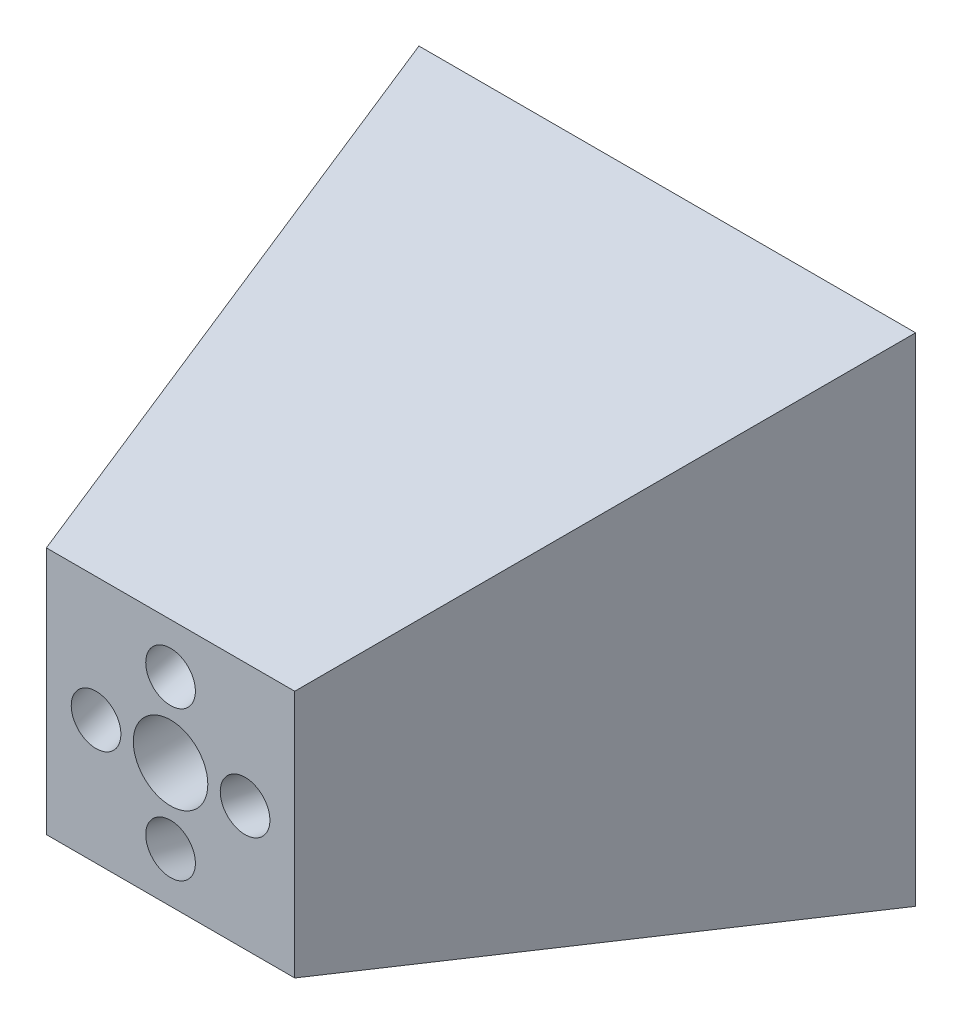
SolidWorks part; units mm, degrees
ref_plane "Front Plane" through (0, 0, 0) normal (0, 0, 1) x (1, 0, 0)
ref_plane "Top Plane" through (0, 0, 0) normal (0, 1, 0) x (1, 0, 0)
ref_plane "Right Plane" through (0, 0, 0) normal (1, 0, 0) x (0, 0, -1)
sketch "Sketch1" plane through (0, 0, 0) normal (0, 0, 1) x (1, 0, 0)
  line L1 (-25000, 25000) -> (25000, 25000)
  line L2 (-25000, 25000) -> (-25000, -25000)
  line L3 (-25000, -25000) -> (25000, -25000)
  line L4 (25000, 25000) -> (25000, -25000)
  point P4 (0, 25000)
  point P5 (25000, 0)
  dimension "D1" = 50000
ref_plane "Plane1" through (0, 0, -100000) normal (0, 0, 1) x (1, 0, 0)
sketch "Sketch2" plane through (0, 0, -100000) normal (0, 0, 1) x (1, 0, 0)
  line L1 (-50000, -50000) -> (50000, -50000)
  line L2 (-50000, -50000) -> (-50000, 50000)
  line L3 (-50000, 50000) -> (50000, 50000)
  line L4 (50000, -50000) -> (50000, 50000)
  line L5 (-50000, -50000) -> (50000, 50000) construction
  line L6 (-50000, 50000) -> (50000, -50000) construction
  point P0 (0, 0)
  dimension "D1" = 100000
loft "Loft1" add profiles "Sketch1", "Sketch2"
sketch "Sketch4" plane through (0, 0, -100000) normal (0, 0, -1) x (-1, 0, 0)
  point P5 (0, 0)
  point P6 (0, 0)
  point P7 (0, 0)
  point P17 (0, 0)
sketch "Sketch12" plane through (0, 0, 0) normal (0, 1, 0) x (1, 0, 0)
  line L0 (0, 100000) -> (0, 0)
sketch "Sketch13" plane through (0, 0, -100000) normal (0, 0, -1) x (-1, 0, 0)
  circle A0 centre (0, 0) radius 7500
  dimension "D1" = 15000
sweep "Cut-Sweep1" cut profiles "Sketch13" path "Sketch12"
sketch "Sketch14" plane through (0, 0, -100000) normal (0, 0, -1) x (-1, 0, 0)
  line L0 (-50000, 50000) -> (50000, 50000) construction
  circle A0 centre (0, 40000) radius 5000
  dimension "D1" = 10000
  dimension "D2" = 10000
sketch "Sketch16" plane through (0, 0, 0) normal (0, 0, 1) x (1, 0, 0)
  circle A0 centre (0, 15000) radius 5000 construction
  dimension "D1" = 10000
  dimension "D2" = 15000
sketch "Sketch17" plane through (0, 0, 0) normal (1, 0, 0) x (0, 0, -1)
  line L0 (100000, 40000) -> (0, 15000)
sweep "Cut-Sweep2" cut profiles "Sketch14" path "Sketch17"
pattern_circular "CirPattern1" count 4 over 360 about axis through (0, 0, -101000) along (0, 0, 1) of "Cut-Sweep2"
